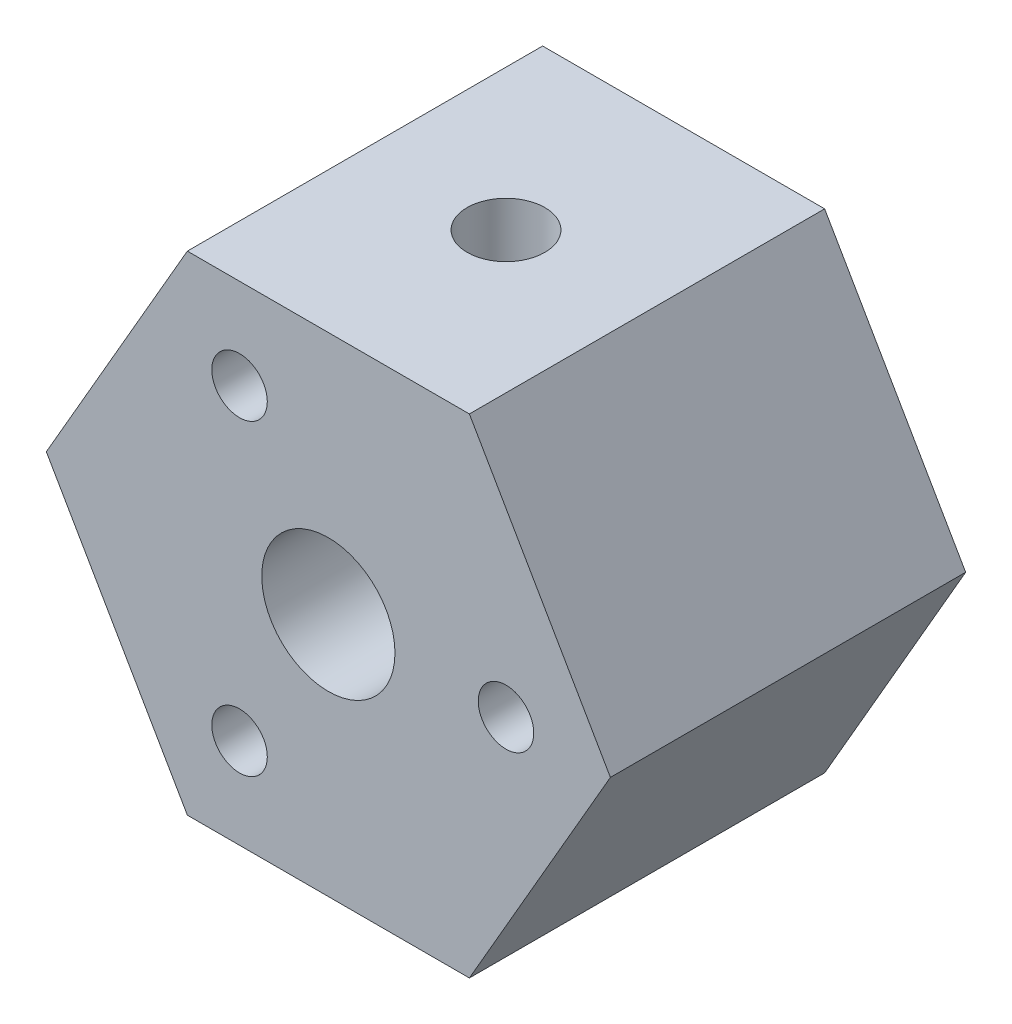
SolidWorks part; units mm, degrees
ref_plane "Plan de face" through (0, 0, 0) normal (0, 0, 1) x (1, 0, 0)
ref_plane "Plan de dessus" through (0, 0, 0) normal (0, 1, 0) x (1, 0, 0)
ref_plane "Plan de droite" through (0, 0, 0) normal (1, 0, 0) x (0, 0, -1)
sketch "Esquisse1" plane through (0, 0, 0) normal (0, 0, 1) x (1, 0, 0)
  line L0 (0, 0) -> (12.7017, 0) construction
  line L1 (12.7017, 0) -> (6.3509, 11)
  line L2 (6.3509, 11) -> (-6.3509, 11)
  line L3 (-6.3509, 11) -> (-12.7017, 0)
  line L4 (-12.7017, 0) -> (-6.3509, -11)
  line L5 (-6.3509, -11) -> (6.3509, -11)
  line L6 (6.3509, -11) -> (12.7017, 0)
  line L7 (0, 0) -> (-6.3509, -11) construction
  line L8 (0, 0) -> (-6.3509, 11) construction
  circle A0 centre (0, 0) radius 11 construction
  circle A1 centre (0, 0) radius 3
  circle A2 centre (0, 0) radius 8 construction
  circle A3 centre (-4, -6.9282) radius 1.25
  circle A4 centre (8, 0) radius 1.25
  circle A5 centre (-4, 6.9282) radius 1.25
  dimension "D1" = 22
  dimension "D2" = 6
  dimension "D3" = 16
  dimension "D4" = 2.5
extrude "Boss.-Extru.1" add sketch "Esquisse1" along normal blind 16
sketch "Esquisse2" plane through (22, -11, 0) normal (0, 1, 0) x (1, 0, 0)
  line L0 (-22, 0) -> (-22, -16) construction
  line L1 (-28.3509, -16) -> (-15.6491, -16) construction
  circle A0 centre (-22, -8) radius 1.75
  dimension "D1" = 3.5
extrude "Enlèv. mat.-Extru.1" cut sketch "Esquisse2" along normal through all
